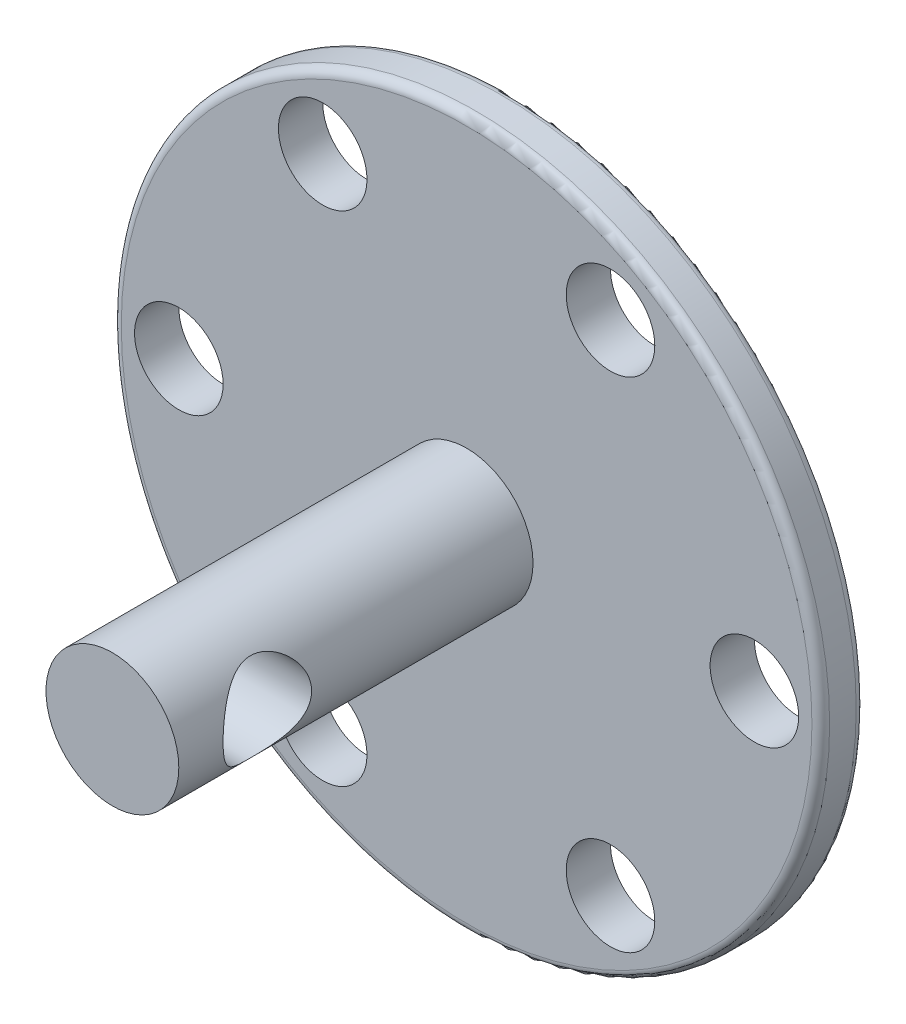
SolidWorks part; units mm, degrees
ref_plane "前视基准面" through (0, 0, 0) normal (0, 0, 1) x (1, 0, 0)
ref_plane "上视基准面" through (0, 0, 0) normal (0, 1, 0) x (1, 0, 0)
ref_plane "右视基准面" through (0, 0, 0) normal (1, 0, 0) x (0, 0, -1)
other "Configuration Table"
sketch "草图1" plane through (0, 0, 0) normal (0, 0, 1) x (1, 0, 0)
  circle A0 centre (0, 0) radius 80
  circle A1 centre (-65, 0) radius 10
  circle A2 centre (-32.5, 56.2917) radius 10
  circle A3 centre (32.5, 56.2917) radius 10
  circle A4 centre (65, 0) radius 10
  circle A5 centre (32.5, -56.2917) radius 10
  circle A6 centre (-32.5, -56.2917) radius 10
  point P20 (0, 0)
  dimension "D2" = 20
  dimension "D4" = 6
extrude "凸台-拉伸1" add sketch "草图1" along normal blind 10
sketch "草图3" plane through (0, 0, 0) normal (0, 0, 1) x (1, 0, 0)
  circle A0 centre (0, 0) radius 15
  dimension "D1" = 30
extrude "凸台-拉伸4" add sketch "草图3" along normal blind 90
sketch "草图4" plane through (0, 0, 0) normal (1, 0, 0) x (0, 0, -1)
  line L0 (-10, 80) -> (-10, -80) construction
  circle A0 centre (-70, 0) radius 10
  dimension "D1" = 20
  dimension "D2" = 60
extrude "切除-拉伸3" cut sketch "草图4" against normal mid plane 90
fillet "圆角1" radius 2 2 edges at (80, 0, 10) (80, 0, 0)
